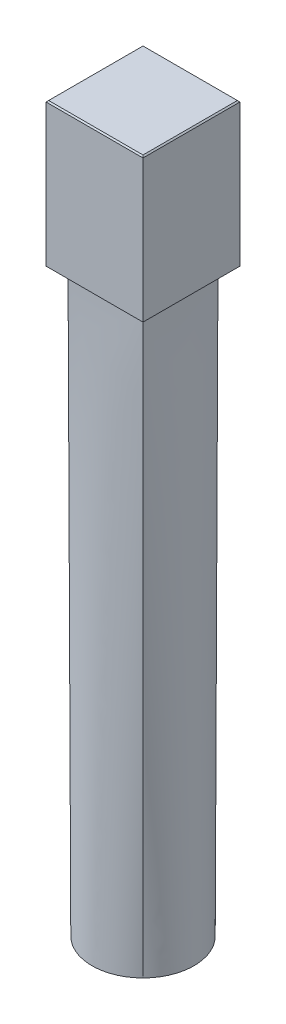
SolidWorks part; units mm, degrees
ref_plane "Front Plane" through (0, 0, 0) normal (0, 0, 1) x (1, 0, 0)
ref_plane "Top Plane" through (0, 0, 0) normal (0, 1, 0) x (1, 0, 0)
ref_plane "Right Plane" through (0, 0, 0) normal (1, 0, 0) x (0, 0, -1)
sketch "Sketch1" plane through (0, 0, 0) normal (0, 1, 0) x (1, 0, 0)
  circle A0 centre (0, 0) radius 1.975
  dimension "D1" = 3.95
ref_plane "Plane1" through (0, 22.4, 0) normal (0, 1, 0) x (1, 0, 0)
sketch "Sketch2" plane through (0, 22.4, 0) normal (0, 1, 0) x (1, 0, 0)
  line L1 (-1.45, -1.45) -> (1.45, -1.45)
  line L2 (-1.45, -1.45) -> (-1.45, 1.45)
  line L3 (-1.45, 1.45) -> (1.45, 1.45)
  line L4 (1.45, -1.45) -> (1.45, 1.45)
  line L5 (-1.45, -1.45) -> (1.45, 1.45) construction
  line L6 (-1.45, 1.45) -> (1.45, -1.45) construction
  point P0 (0, 0)
  dimension "D1" = 2.9
loft "Loft1" add profiles "Sketch1", "Sketch2"
sketch "Sketch3" plane through (0, 22.4, 0) normal (0, 1, 0) x (1, 0, 0)
  line L1 (-1.875, -1.875) -> (1.875, -1.875)
  line L2 (-1.875, -1.875) -> (-1.875, 1.875)
  line L3 (-1.875, 1.875) -> (1.875, 1.875)
  line L4 (1.875, -1.875) -> (1.875, 1.875)
  line L5 (-1.875, -1.875) -> (1.875, 1.875) construction
  line L6 (-1.875, 1.875) -> (1.875, -1.875) construction
  point P0 (0, 0)
  dimension "D1" = 3.75
extrude "Boss-Extrude4" add sketch "Sketch3" along normal blind 5.6
chamfer "Chamfer1" distance 0.05 angle 45 8 edges at (0, 28, 1.875) (1.875, 28, 0) (-1.875, 28, 0) (0, 28, -1.875) (1.875, 22.4, 0) (0, 22.4, -1.875) (-1.875, 22.4, 0) (0, 22.4, 1.875)
